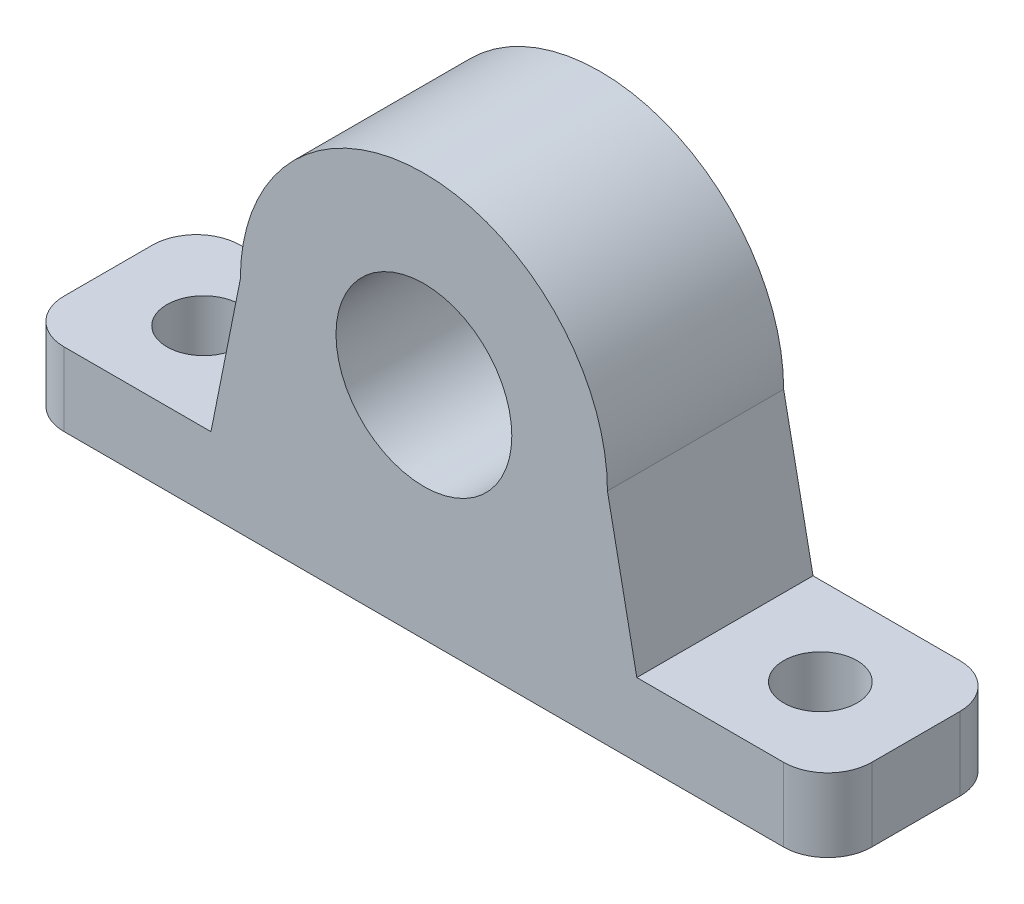
SolidWorks part; units mm, degrees
ref_plane "Front Plane" through (0, 0, 0) normal (0, 0, 1) x (1, 0, 0)
ref_plane "Top Plane" through (0, 0, 0) normal (0, 1, 0) x (1, 0, 0)
ref_plane "Right Plane" through (0, 0, 0) normal (1, 0, 0) x (0, 0, -1)
sketch "Sketch5" plane through (0, 0, 0) normal (0, 0, 1) x (1, 0, 0)
  line L0 (0, 0) -> (55, 0)
  line L1 (55, 0) -> (55, 5)
  line L2 (55, 5) -> (42, 5)
  line L5 (13, 5) -> (0, 5)
  line L6 (0, -55) -> (0, 55) construction
  line L7 (0, 5) -> (0, 0)
  line L8 (27.5, -984.714) -> (27.5, 49015.286) construction
  line L9 (13, 5) -> (15, 15)
  line L10 (40, 15) -> (42, 5)
  arc A0 (40, 15) -> (15, 15) centre (27.5, 15) ccw
  dimension "D5" = 12.5
  dimension "D1" = 55
  dimension "D2" = 5
  dimension "D3" = 13
  dimension "D4" = 13
  dimension "D6" = 27.5
  dimension "D7" = 5
  dimension "D8" = 15
extrude "Boss-Extrude3" add sketch "Sketch5" along normal blind 12 contours L10 L2 L1 L0 L7 L5 L9 A0
sketch "Sketch7" plane through (0, 0, 0) normal (0, 0, -1) x (-1, 0, 0)
  line L0 (0, 6.6) -> (0, -6.6) construction
  circle A0 centre (-27.5, 15) radius 5.987
  dimension "D1" = 27.5
  dimension "D2" = 15
extrude "Cut-Extrude1" cut sketch "Sketch7" against normal up to surface (12 mm away) up to face at (27.5, 7.8125, 12)
sketch "Sketch9" plane through (0, 0, 0) normal (0, 1, 0) x (1, 0, 0)
  line L0 (27.5, -996.0443) -> (27.5, 49003.9557) construction
  line L1 (-972.5, -6) -> (49027.5, -6) construction
  line L3 (0, -12) -> (0, 0) construction
  circle A0 centre (6.5, -6) radius 2.5
  circle A1 centre (48.5, -6) radius 2.5
  dimension "D3" = 5
  dimension "D4" = 6.5
  dimension "D1" = 27.5
  dimension "D2" = 6
extrude "Cut-Extrude2" cut sketch "Sketch9" along normal up to surface (5 mm away) up to face at (6.5, 5, 6)
fillet "Fillet2" radius 3 4 edges at (55, 2.5, 0) (55, 2.5, 12) (0, 2.5, 12) (0, 2.5, 0)
